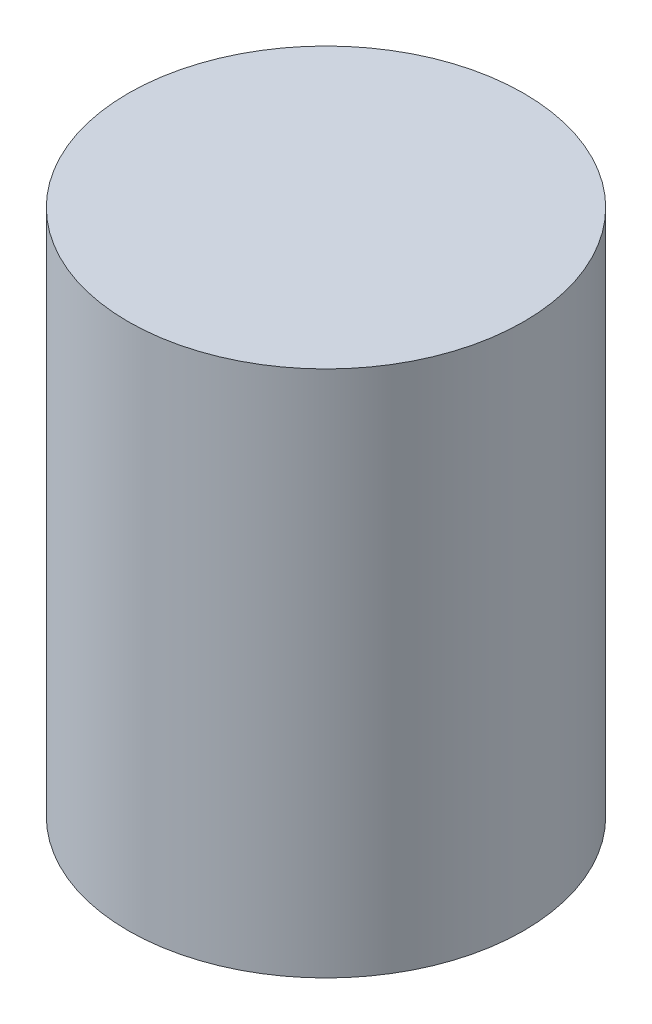
SolidWorks part; units mm, degrees
ref_plane "Alzado" through (0, 0, 0) normal (0, 0, 1) x (1, 0, 0)
ref_plane "Planta" through (0, 0, 0) normal (0, 1, 0) x (1, 0, 0)
ref_plane "Vista lateral" through (0, 0, 0) normal (1, 0, 0) x (0, 0, -1)
sketch "Croquis2" plane through (0, 0, 0) normal (0, 1, 0) x (1, 0, 0)
  circle A0 centre (0, 0) radius 15
  dimension "D1" = 30
extrude "Saliente-Extruir1" add sketch "Croquis2" along normal blind 40
